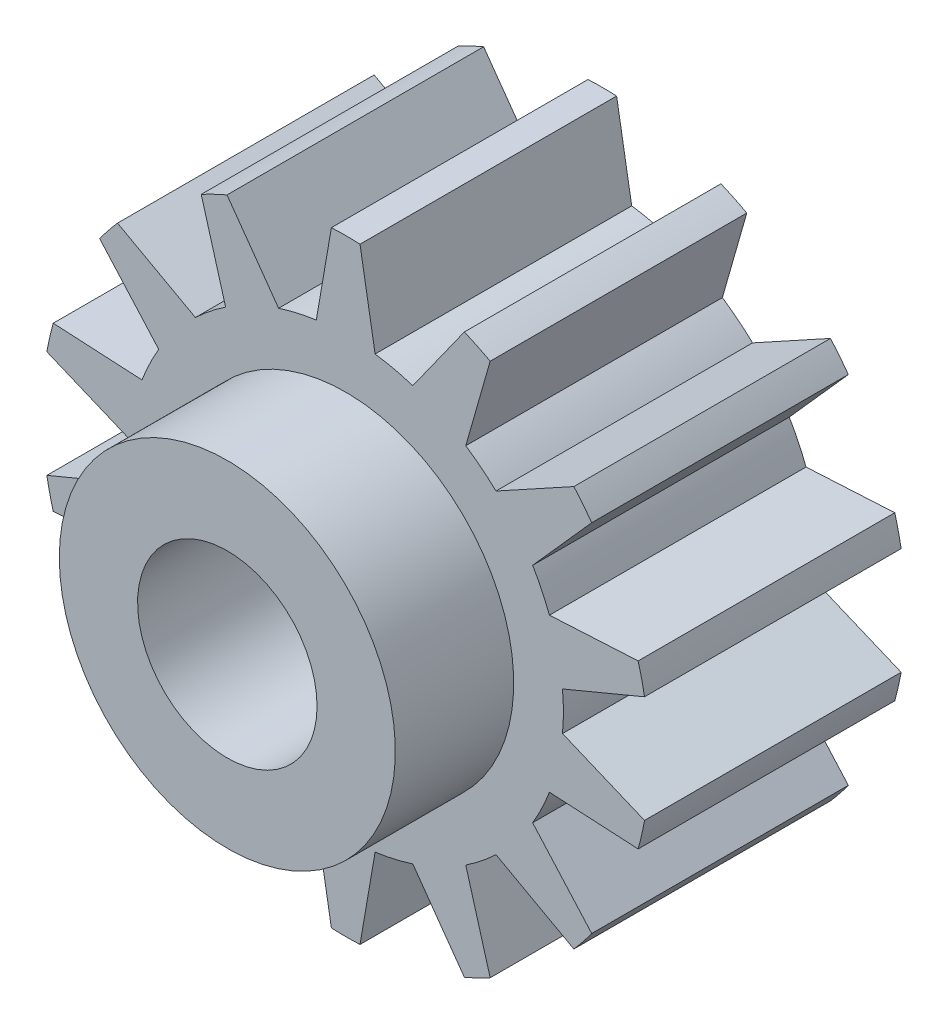
SolidWorks part; units mm, degrees
material "PW50:30:C1:0:1:2:Re:16:"
ref_plane "Plane1" through (0, 0, 0) normal (0, 0, 1) x (1, 0, 0)
ref_plane "Plane2" through (0, 0, 0) normal (0, 1, 0) x (1, 0, 0)
ref_plane "Plane3" through (0, 0, 0) normal (1, 0, 0) x (0, 0, -1)
other "Configuration Table"
sketch "Sketch1" plane through (0, 0, 0) normal (0, 0, 1) x (1, 0, 0)
  line L0 (0, 10.9008) -> (0, -10.045) construction
  circle A1 centre (0, 0) radius 5.7
  dimension "D1" = 11.4
extrude "motor gear shape" add sketch "Sketch1" along normal blind 6.72
sketch "Sketch2" plane through (0, 0, 6.72) normal (0, 0, 1) x (1, 0, 0)
  line L0 (0, 9.1728) -> (0, -9.6432) construction
  line L1 (0.375, 7.9412) -> (0.77, 5.6478)
  line L2 (-0.375, 7.9412) -> (-0.77, 5.6478)
  arc A0 (0.375, 7.9412) -> (-0.375, 7.9412) centre (0, 0) ccw
  circle A1 centre (0, 0) radius 5.7 construction
  arc A2 (0.77, 5.6478) -> (-0.77, 5.6478) centre (0, 0) ccw
  dimension "D1" = 15.9
  dimension "D2" = 0.75
  dimension "D3" = 1.54
extrude "motor gear tooth" add sketch "Sketch2" along normal up to surface (6.72 mm away)
pattern_circular "motor gear teeth " count 14 every 25.714 about axis through (0, 0, 0) along (0, 0, 1) of "motor gear tooth"
sketch "Sketch3" plane through (0, 0, 6.72) normal (0, 0, 1) x (1, 0, 0)
  circle A0 centre (0, 0) radius 4.4
  circle A1 centre (0, 0) radius 2.35
  dimension "D1" = 8.8
  dimension "D2" = 4.7
extrude "motor gear boss" add sketch "Sketch3" along normal blind 3.1
sketch "Sketch4" plane through (0, 0, 9.82) normal (0, 0, 1) x (1, 0, 0)
  circle A0 centre (0, 0) radius 2.35 construction
  circle A1 centre (0, 0) radius 2.35
extrude "motor shaft hole" cut sketch "Sketch4" against normal through all
sketch "Sketch5" plane through (0, 0, 0) normal (0, 0, -1) x (-1, 0, 0)
  line L0 (-3.1081, -1.25) -> (3.1081, -1.25)
  circle A2 centre (0, 0) radius 3.35
  arc A3 (-3.1081, -1.25) -> (3.1081, -1.25) centre (0, 0) ccw
  circle A4 centre (0, 0) radius 2.35 construction
  dimension "D1" = 1
  dimension "D2" = 3.6
extrude "motor shaft flat" add sketch "Sketch5" against normal blind 4.9
